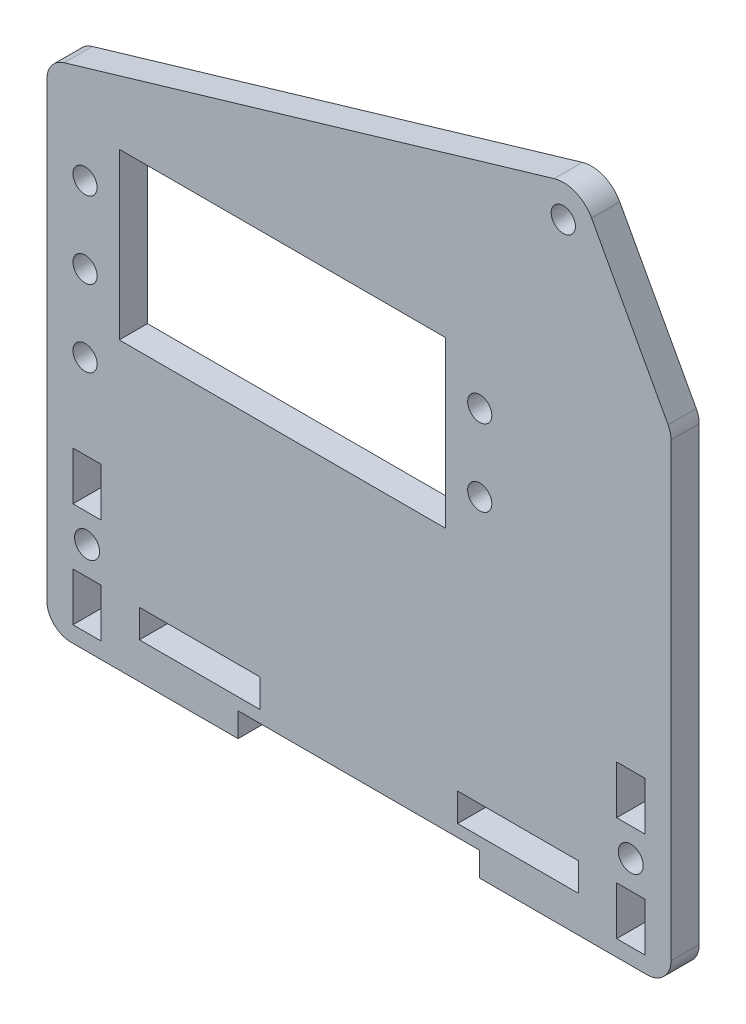
SolidWorks part; units mm, degrees
material "Balsa"
ref_plane "Front Plane" through (0, 0, 0) normal (0, 0, 1) x (1, 0, 0)
ref_plane "Top Plane" through (0, 0, 0) normal (0, 1, 0) x (1, 0, 0)
ref_plane "Right Plane" through (0, 0, 0) normal (1, 0, 0) x (0, 0, -1)
sketch "Sketch1" plane through (0, 0, 0) normal (0, 0, 1) x (1, 0, 0)
  line L0 (27.1713, 45) -> (23.5724, 45) construction
  line L1 (-35.75, -31) -> (35.75, -31)
  line L2 (-38.75, -28) -> (-38.75, 28)
  line L3 (-36.1835, 31) -> (36.1835, 31) construction
  line L4 (38.75, -28) -> (38.75, 28)
  line L5 (0, 31) -> (0, -31) construction
  line L6 (-38.75, 0) -> (38.75, 0) construction
  line L7 (-29.75, 4.5) -> (10.75, 4.5)
  line L8 (-29.75, 4.5) -> (-29.75, 25)
  line L9 (-29.75, 25) -> (10.75, 25)
  line L10 (10.75, 4.5) -> (10.75, 25)
  line L11 (25.3718, 54.2026) -> (25.3718, 47.4582) construction
  line L12 (24.2394, 48.8363) -> (-36.5993, 30.8773)
  line L13 (28.8863, 46.9102) -> (38.3858, 29.4326)
  line L14 (10.75, 14.75) -> (-29.75, 14.75) construction
  line L15 (-19.36, 18.0838) -> (-19.36, 11.4162) construction
  arc A0 (38.3858, 29.4326) -> (38.75, 28) centre (35.75, 28) cw
  arc A1 (35.75, -31) -> (38.75, -28) centre (35.75, -28) ccw
  arc A2 (-35.75, -31) -> (-38.75, -28) centre (-35.75, -28) cw
  arc A3 (-38.75, 28) -> (-36.5993, 30.8773) centre (-35.75, 28) cw
  circle A4 centre (25.3718, 45) radius 1.5
  arc A5 (24.2394, 48.8363) -> (28.8863, 46.9102) centre (25.3718, 45) cw
  point P0 (0, 0)
  point P8 (38.75, -31)
  point P12 (-38.75, -31)
  point P33 (-19.36, 14.75)
  dimension "D2" = 3
  dimension "D3" = 62
  dimension "D10" = 3
  dimension "D11" = 4
  dimension "D1" = 28
  dimension "D4" = 40.5
  dimension "D5" = 20.5
  dimension "D6" = 9
  dimension "D7" = 6
  dimension "D8" = 54
  dimension "D9" = 20
  dimension "D12" = 10.39
extrude "Boss-Extrude1" add sketch "Sketch1" along normal blind 3.5
sketch "Sketch2" plane through (0, 0, 0) normal (0, 0, -1) x (-1, 0, 0)
  line L0 (-38.75, -19.5) -> (38.75, -19.5) construction
  line L1 (-38.75, -28) -> (-38.75, 28) construction
  line L2 (38.75, 28) -> (38.75, -28) construction
  line L3 (35.75, -31) -> (-35.75, -31) construction
  line L4 (-33.75, -8) -> (-33.75, -31) construction
  line L5 (0, 9.9619) -> (0, -7.9273) construction
  line L6 (-35.5, -16) -> (-32, -16)
  line L7 (-35.5, -16) -> (-35.5, -10)
  line L8 (-35.5, -10) -> (-32, -10)
  line L9 (-32, -16) -> (-32, -10)
  line L10 (-33.75, -10) -> (-33.75, -16) construction
  line L11 (-35.5, -13) -> (-32, -13) construction
  line L12 (-35.5, -29) -> (-32, -29)
  line L13 (-35.5, -29) -> (-35.5, -23)
  line L14 (-35.5, -23) -> (-32, -23)
  line L15 (-32, -29) -> (-32, -23)
  line L16 (-33.75, -23) -> (-33.75, -29) construction
  line L17 (-35.5, -26) -> (-32, -26) construction
  line L18 (35.5, -29) -> (32, -29)
  line L19 (35.5, -29) -> (35.5, -23)
  line L20 (35.5, -23) -> (32, -23)
  line L21 (32, -29) -> (32, -23)
  line L22 (35.5, -16) -> (32, -16)
  line L23 (35.5, -16) -> (35.5, -10)
  line L24 (35.5, -10) -> (32, -10)
  line L25 (32, -16) -> (32, -10)
  circle A0 centre (-33.75, -19.5) radius 1.55
  circle A1 centre (33.75, -19.5) radius 1.55
  point P10 (-33.75, -13)
  point P14 (-33.75, -26)
  dimension "D8" = 3.1
  dimension "D1" = 11.5
  dimension "D2" = 5
  dimension "D3" = 3.5
  dimension "D4" = 6
  dimension "D5" = 6
  dimension "D6" = 19
  dimension "D9" = 0
extrude "Cut-Extrude1" cut sketch "Sketch2" against normal through all
sketch "Sketch3" plane through (0, 0, 0) normal (0, 0, -1) x (-1, 0, 0)
  line L0 (-32, -23) -> (32, -23) construction
  line L1 (0, 0) -> (0, -31.4864) construction
  line L2 (27.25, -23) -> (27.25, -26.5)
  line L3 (-27.25, -23) -> (-12.25, -23)
  line L4 (-27.25, -23) -> (-27.25, -26.5)
  line L5 (-27.25, -26.5) -> (-12.25, -26.5)
  line L6 (-12.25, -23) -> (-12.25, -26.5)
  line L7 (27.25, -23) -> (12.25, -23)
  line L8 (12.25, -23) -> (12.25, -26.5)
  line L9 (27.25, -26.5) -> (12.25, -26.5)
  dimension "D1" = 24.5
  dimension "D2" = 15
  dimension "D3" = 3.5
extrude "Cut-Extrude2" cut sketch "Sketch3" against normal through all
sketch "Sketch4" plane through (0, 0, 0) normal (0, 0, -1) x (-1, 0, 0)
  line L0 (-15, 14.75) -> (29.75, 14.75) construction
  line L1 (9.5, 28.7883) -> (9.5, -1.2827) construction
  line L2 (-10.75, 25) -> (29.75, 25) construction
  line L3 (29.75, 4.5) -> (-10.75, 4.5) construction
  line L4 (29.75, 25) -> (29.75, 4.5) construction
  line L5 (-10.75, 4.5) -> (-10.75, 25) construction
  line L7 (-15, 10) -> (34, 10) construction
  line L8 (-15, 10) -> (-15, 19.5) construction
  line L9 (-15, 19.5) -> (34, 19.5) construction
  line L10 (34, 10) -> (34, 19.5) construction
  line L11 (9.5, 19.5) -> (9.5, 10) construction
  line L12 (-15, 14.75) -> (34, 14.75) construction
  circle A0 centre (-15, 19.5) radius 1.5
  circle A1 centre (-15, 10) radius 1.5
  circle A2 centre (34, 10) radius 1.5
  circle A3 centre (34, 19.5) radius 1.5
  point P12 (9.5, 14.75)
  dimension "D3" = 3
  dimension "D1" = 9.5
  dimension "D2" = 49
extrude "Cut-Extrude3" cut sketch "Sketch4" against normal through all
sketch "Sketch5" plane through (0, 0, 0) normal (0, 0, -1) x (-1, 0, 0)
  line L0 (34, -31) -> (34, 31.6446) construction
  line L3 (35.75, -31) -> (-35.75, -31) construction
  line L4 (-24.2394, 48.8363) -> (36.5993, 30.8773) construction
  circle A0 centre (34, 0.5) radius 1.5
  circle A8 centre (34, 19.5) radius 1.5 construction
  circle A10 centre (34, 19.5) radius 1.5
  circle A11 centre (34, 10) radius 1.5 construction
  circle A12 centre (34, 10) radius 1.5
  dimension "D1" = 2
extrude "Cut-Extrude5" cut sketch "Sketch5" against normal up to next contours A0
sketch "Sketch6" plane through (0, 0, 3.5) normal (0, 0, 1) x (1, 0, 0)
  line L0 (0, 9.3086) -> (0, -38.9466) construction
  line L1 (-35.75, -31) -> (35.75, -31) construction
  line L2 (-15, -28) -> (15, -28)
  line L3 (-15, -28) -> (-15, -31)
  line L4 (-15, -31) -> (15, -31)
  line L5 (15, -28) -> (15, -31)
  line L6 (-15, -28) -> (15, -31) construction
  line L7 (-15, -31) -> (15, -28) construction
  point P3 (0, -29.5)
  dimension "D1" = 3
  dimension "D2" = 30
extrude "Cut-Extrude6" cut sketch "Sketch6" against normal blind 10
